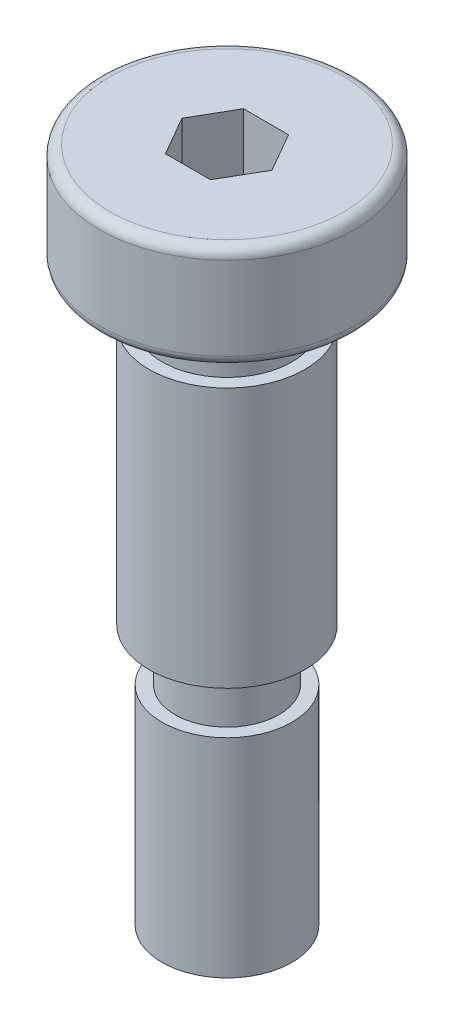
SolidWorks part; units mm, degrees
material "AISI 304"
ref_plane "前视基准面" through (0, 0, 0) normal (0, 0, 1) x (1, 0, 0)
ref_plane "上视基准面" through (0, 0, 0) normal (0, 1, 0) x (1, 0, 0)
ref_plane "右视基准面" through (0, 0, 0) normal (1, 0, 0) x (0, 0, -1)
sketch "草图1" plane through (0, 0, 0) normal (0, 0, 1) x (1, 0, 0)
  line L0 (0, 0) -> (0, 26) construction
  line L1 (0, 26) -> (-4.5, 26)
  line L2 (-4.9, 25.6) -> (-4.9, 22.4)
  line L3 (-4.5, 22) -> (-2.5, 22)
  line L4 (-2.5, 22) -> (-2.5, 20)
  line L5 (-2.5, 20) -> (-3, 20)
  line L6 (-3, 20) -> (-3, 10)
  line L7 (-3, 10) -> (-2, 10)
  line L8 (-2, 10) -> (-2, 8)
  line L9 (-2, 8) -> (-2.5, 8)
  line L10 (-2.5, 8) -> (-2.5, 0)
  line L11 (-2.5, 0) -> (0, 0)
  line L12 (0, 0) -> (0, 26)
  arc A0 (-4.9, 22.4) -> (-4.5, 22) centre (-4.5, 22.4) ccw
  arc A1 (-4.5, 26) -> (-4.9, 25.6) centre (-4.5, 25.6) ccw
  point P17 (-4.9, 22)
  point P20 (-4.9, 26)
  dimension "D11" = 0.4
  dimension "D1" = 4
  dimension "D2" = 9.8
  dimension "D3" = 6
  dimension "D4" = 2
  dimension "D5" = 0.5
  dimension "D6" = 10
  dimension "D7" = 5
  dimension "D8" = 4
  dimension "D9" = 2
  dimension "D10" = 12
revolve "旋转1" add sketch "草图1" angle 360 about L0
cosmetic thread "装饰螺纹线1" parameters "D2"=4.11
sketch "草图2" plane through (0, 26, 0) normal (0, 1, 0) x (1, 0, 0)
  line L1 (0.866, 1.5) -> (-0.866, 1.5)
  line L2 (-0.866, 1.5) -> (-1.7321, 0)
  line L3 (-1.7321, 0) -> (-0.866, -1.5)
  line L4 (-0.866, -1.5) -> (0.866, -1.5)
  line L5 (0.866, -1.5) -> (1.7321, 0)
  line L6 (1.7321, 0) -> (0.866, 1.5)
  circle A0 centre (0, 0) radius 1.5 construction
  dimension "D1" = 3
extrude "切除-拉伸1" cut sketch "草图2" against normal blind 3.5
